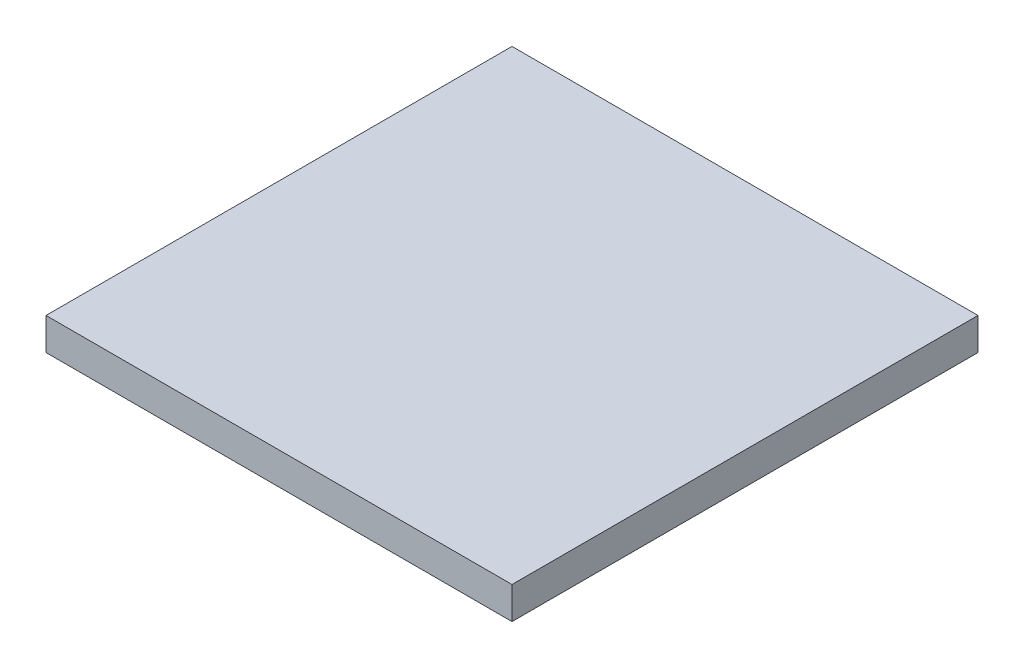
SolidWorks part; units mm, degrees
ref_plane "前视基准面" through (0, 0, 0) normal (0, 0, 1) x (1, 0, 0)
ref_plane "上视基准面" through (0, 0, 0) normal (0, 1, 0) x (1, 0, 0)
ref_plane "右视基准面" through (0, 0, 0) normal (1, 0, 0) x (0, 0, -1)
sketch "草图1" plane through (0, 0, 0) normal (0, 1, 0) x (1, 0, 0)
  line L1 (-29, 29) -> (29, 29)
  line L2 (-29, 29) -> (-29, -29)
  line L3 (-29, -29) -> (29, -29)
  line L4 (29, 29) -> (29, -29)
  line L5 (-29, 29) -> (29, -29) construction
  line L6 (-29, -29) -> (29, 29) construction
  point P0 (0, 0)
  dimension "D1" = 58
  dimension "D2" = 58
extrude "凸台-拉伸1" add sketch "草图1" along normal blind 4
